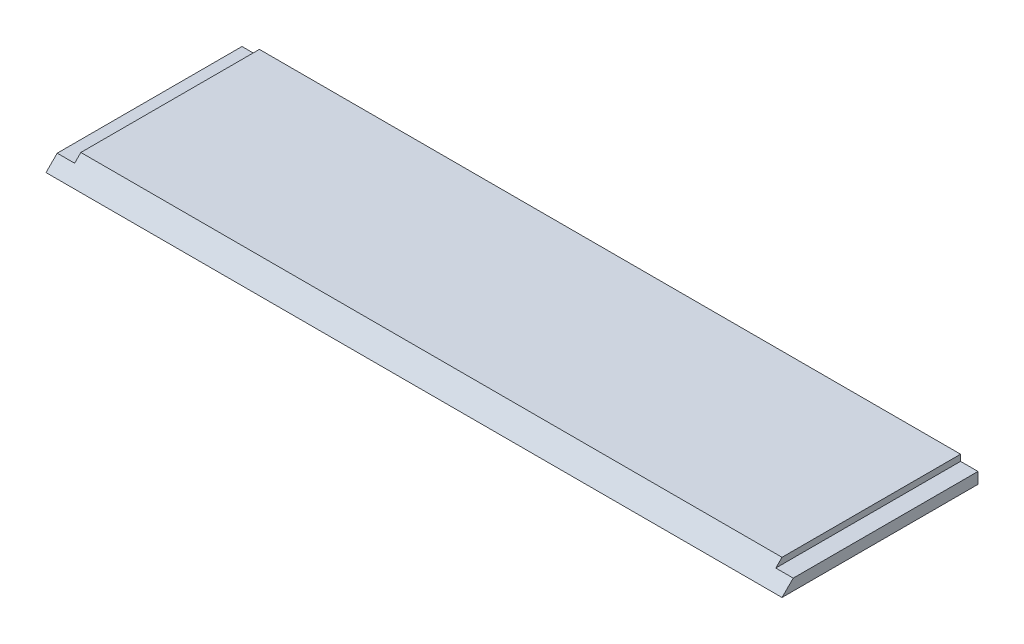
SolidWorks part; units mm, degrees
material "柚木"
ref_plane "前视基准面" through (0, 0, 0) normal (0, 0, 1) x (1, 0, 0)
ref_plane "上视基准面" through (0, 0, 0) normal (0, 1, 0) x (1, 0, 0)
ref_plane "右视基准面" through (0, 0, 0) normal (1, 0, 0) x (0, 0, -1)
sketch "草图1" plane through (0, 0, 0) normal (0, 1, 0) x (1, 0, 0)
  line L1 (-54.5007, 28.8001) -> (63.7993, 28.8001)
  line L2 (-54.5007, 28.8001) -> (-54.5007, -2.6999)
  line L3 (-54.5007, -2.6999) -> (63.7993, -2.6999)
  line L4 (63.7993, 28.8001) -> (63.7993, -2.6999)
  dimension "D1" = 118.3
  dimension "D2" = 31.5
extrude "凸台-拉伸1" add sketch "草图1" along normal blind 2.8
sketch "草图2" plane through (63.7993, 0, 0) normal (1, 0, 0) x (0, 0, -1)
  line L0 (-2.6999, 0) -> (-2.6999, 2.8)
  line L1 (-2.6999, 2.8) -> (0.1001, 2.8)
  line L2 (-2.6999, 2.8) -> (28.8001, 2.8) construction
  line L3 (0.1001, 2.8) -> (-2.6999, 0)
  dimension "D1" = 45
extrude "切除-拉伸1" cut sketch "草图2" against normal through all
sketch "草图3" plane through (0, 2.8, 0) normal (0, 1, 0) x (1, 0, 0)
  line L0 (-54.5007, -2.6999) -> (63.7993, -2.6999) construction
  line L1 (-54.5007, 28.8001) -> (-51.7007, 28.8001)
  line L2 (-54.5007, 28.8001) -> (-54.5007, -2.6999)
  line L3 (-54.5007, -2.6999) -> (-51.7007, -2.6999)
  line L4 (-51.7007, 28.8001) -> (-51.7007, -2.6999)
  line L5 (63.7993, 0.1001) -> (63.7993, 28.8001) construction
  line L6 (63.7993, 28.8001) -> (60.9993, 28.8001)
  line L7 (63.7993, 28.8001) -> (63.7993, -2.6999)
  line L8 (63.7993, -2.6999) -> (60.9993, -2.6999)
  line L9 (60.9993, 28.8001) -> (60.9993, -2.6999)
  line L10 (63.7993, 28.8001) -> (-54.5007, 28.8001) construction
  dimension "D1" = 2.8
  dimension "D2" = 2.8
extrude "切除-拉伸2" cut sketch "草图3" against normal blind 1
